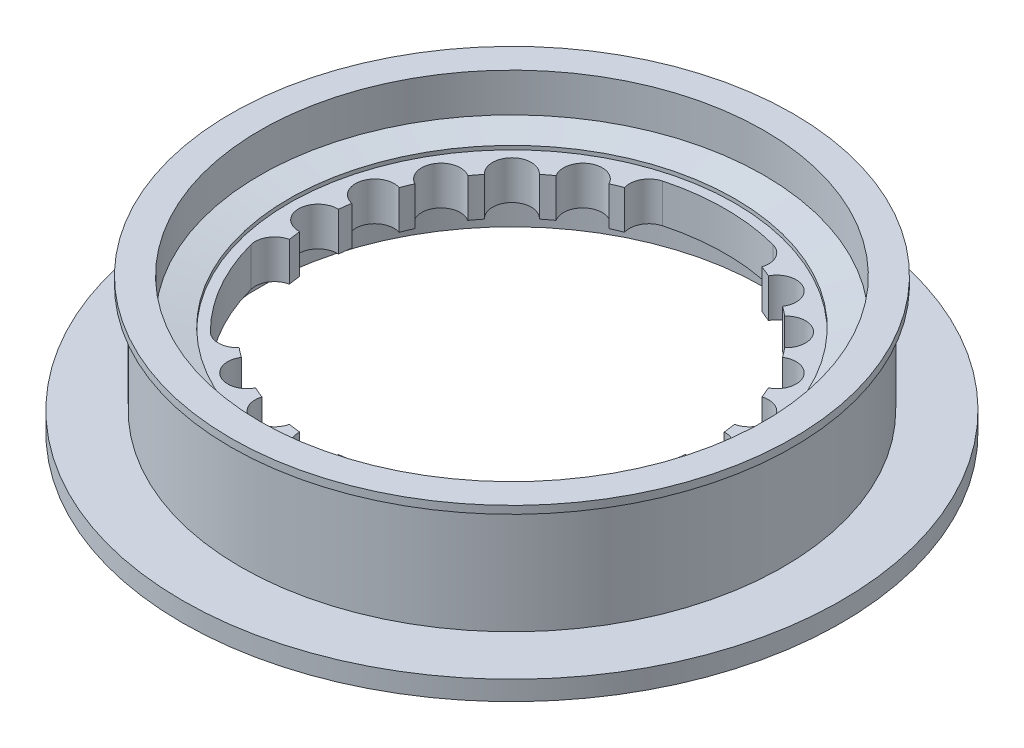
SolidWorks part; units mm, degrees
ref_plane "前视基准面" through (0, 0, 0) normal (0, 0, 1) x (1, 0, 0)
ref_plane "上视基准面" through (0, 0, 0) normal (0, 1, 0) x (1, 0, 0)
ref_plane "右视基准面" through (0, 0, 0) normal (1, 0, 0) x (0, 0, -1)
sketch "草图1" plane through (0, 0, 0) normal (0, 1, 0) x (1, 0, 0)
  circle A0 centre (0, 0) radius 17
  dimension "D1" = 34
extrude "凸台-拉伸1" add sketch "草图1" along normal blind 1
sketch "草图2" plane through (0, 1, 0) normal (0, 1, 0) x (1, 0, 0)
  circle A0 centre (0, 0) radius 14
  dimension "D1" = 28
extrude "凸台-拉伸2" add sketch "草图2" along normal blind 5.6
sketch "草图3" plane through (0, 6.6, 0) normal (0, 1, 0) x (1, 0, 0)
  circle A0 centre (0, 0) radius 14.5
  dimension "D1" = 29
extrude "凸台-拉伸3" add sketch "草图3" along normal blind 0.4
sketch "草图4" plane through (0, 0, 0) normal (1, 0, 0) x (0, 0, -1)
  line L0 (0, 0) -> (13, 0)
  line L1 (-17, 0) -> (17, 0) construction
  line L2 (13, 0) -> (13, 2)
  line L3 (13, 2) -> (11.5, 2.3)
  line L4 (11.5, 2.3) -> (11.5, 2.5)
  line L5 (11.5, 2.5) -> (0, 2.5)
  line L6 (0, 2.5) -> (0, 0)
  line L7 (0, 2.5) -> (0, 3.5) construction
  line L8 (0, 3.5) -> (5.9564, 3.5) construction
  line L9 (11.5, 4.7) -> (11.5, 4.5)
  line L10 (13, 5) -> (11.5, 4.7)
  line L11 (13, 7) -> (13, 5)
  line L12 (0, 7) -> (13, 7)
  line L13 (0, 4.5) -> (0, 7)
  line L14 (11.5, 4.5) -> (0, 4.5)
  dimension "D1" = 13
  dimension "D2" = 2
  dimension "D3" = 2.5
  dimension "D4" = 0.2
  dimension "D5" = 11.5
  dimension "D6" = 1
revolve "切除-旋转1" cut sketch "草图4" angle 360 about L13
sketch "草图5" plane through (0, 4.5, 0) normal (0, 1, 0) x (1, 0, 0)
  line L0 (0, 0) -> (0, 10) construction
  arc A0 (-3.54, 9.3525) -> (-4.1101, 9.1163) centre (0, 0) ccw
  arc A1 (-3.54, 9.3525) -> (-6.3295, 7.7419) centre (0, 0) ccw
  circle A2 centre (0, 10) radius 1 construction
  arc A3 (3.54, 9.3525) -> (2.847, 10.6252) centre (2.5882, 9.6593) ccw
  arc A4 (-9.1163, 4.1101) -> (-9.3525, 3.54) centre (0, 0) ccw
  arc A5 (5.8399, 8.1176) -> (4.1101, 9.1163) centre (5, 8.6603) ccw
  arc A6 (-9.95, -0.9987) -> (-9.8695, -1.6105) centre (0, 0) ccw
  arc A7 (7.7419, 6.3295) -> (6.3295, 7.7419) centre (7.0711, 7.0711) ccw
  arc A8 (-6.3295, -7.7419) -> (-5.8399, -8.1176) centre (0, 0) ccw
  arc A9 (9.1163, 4.1101) -> (8.1176, 5.8399) centre (8.6603, 5) ccw
  arc A10 (-1.6105, -9.8695) -> (-0.9987, -9.95) centre (0, 0) ccw
  arc A11 (9.8695, 1.6105) -> (9.3525, 3.54) centre (9.6593, 2.5882) ccw
  arc A12 (2.9237, -9.563) -> (4.1101, -9.1163) centre (0, 0) ccw
  arc A13 (9.95, -0.9987) -> (9.95, 0.9987) centre (10, 0) ccw
  arc A14 (9.95, 0.9987) -> (9.8695, 1.6105) centre (0, 0) ccw
  arc A15 (10.6252, -2.847) -> (9.8695, -1.6105) centre (9.6593, -2.5882) ccw
  arc A16 (7.7419, -6.3295) -> (8.1176, -5.8399) centre (0, 0) ccw
  arc A17 (9.8695, -1.6105) -> (9.95, -0.9987) centre (0, 0) ccw
  arc A18 (9.1163, -4.1101) -> (9.1163, 4.1101) centre (0, 0) ccw
  arc A19 (6.3295, -7.7419) -> (7.7782, -7.7782) centre (7.0711, -7.0711) ccw
  arc A20 (6.3295, 7.7419) -> (5.8399, 8.1176) centre (0, 0) ccw
  arc A21 (4.1101, -9.1163) -> (5.8399, -8.1176) centre (5, -8.6603) ccw
  arc A23 (1.6105, -9.8695) -> (3.54, -9.3525) centre (2.5882, -9.6593) ccw
  arc A25 (-0.9987, -9.95) -> (0.9987, -9.95) centre (0, -10) ccw
  circle A26 centre (0, 0) radius 10 construction
  arc A27 (-3.54, -9.3525) -> (-1.6105, -9.8695) centre (-2.5882, -9.6593) ccw
  circle A28 centre (0, 0) radius 10 construction
  arc A29 (-5.8399, -8.1176) -> (-4.1101, -9.1163) centre (-5, -8.6603) ccw
  circle A30 centre (0, 0) radius 10
  arc A31 (-7.7782, -7.7782) -> (-6.3295, -7.7419) centre (-7.0711, -7.0711) ccw
  circle A32 centre (0, 0) radius 10
  arc A33 (-4.1101, -9.1163) -> (-9.1163, -4.1101) centre (0, 0) ccw
  circle A34 centre (0, 0) radius 10
  arc A35 (-9.8695, -1.6105) -> (-10.6252, -2.847) centre (-9.6593, -2.5882) ccw
  circle A36 centre (0, 0) radius 10
  arc A37 (-9.95, 0.9987) -> (-9.95, -0.9987) centre (-10, 0) ccw
  circle A38 centre (0, 0) radius 10
  arc A39 (-9.3525, 3.54) -> (-9.8695, 1.6105) centre (-9.6593, 2.5882) ccw
  circle A40 centre (0, 0) radius 10
  arc A41 (-8.1176, 5.8399) -> (-9.1163, 4.1101) centre (-8.6603, 5) ccw
  circle A42 centre (0, 0) radius 10
  arc A43 (-6.3295, 7.7419) -> (-7.7419, 6.3295) centre (-7.0711, 7.0711) ccw
  circle A44 centre (0, 0) radius 10
  arc A45 (-4.1101, 9.1163) -> (-5.8399, 8.1176) centre (-5, 8.6603) ccw
  circle A46 centre (0, 0) radius 10
  arc A47 (-2.847, 10.6252) -> (-3.54, 9.3525) centre (-2.5882, 9.6593) ccw
  arc A48 (-10.6252, -2.847) -> (-7.7782, -7.7782) centre (0, 0) ccw
  arc A49 (0, 10) -> (-0.9987, 9.95) centre (0, 0) ccw
  arc A50 (-5.8399, 8.1176) -> (3.54, 9.3525) centre (0, 0) ccw
  arc A51 (-7.7419, 6.3295) -> (-0.9987, 9.95) centre (0, 0) ccw
  arc A52 (-9.8695, 1.6105) -> (-8.1176, 5.8399) centre (0, 0) ccw
  arc A53 (-9.1163, -4.1101) -> (-9.95, 0.9987) centre (0, 0) ccw
  arc A54 (-8.1176, -5.8399) -> (-9.1163, -4.1101) centre (-8.6603, -5) ccw [skipped]
  arc A55 (0.9987, -9.95) -> (-3.54, -9.3525) centre (0, 0) ccw
  arc A56 (5.8399, -8.1176) -> (1.6105, -9.8695) centre (0, 0) ccw
  arc A57 (9.1163, -4.1101) -> (6.3295, -7.7419) centre (0, 0) ccw
  arc A58 (9.5263, -5.5) -> (9.1163, -4.1101) centre (8.6603, -5) ccw [skipped]
  arc A59 (7.7419, -6.3295) -> (8.1176, -5.8399) centre (0, 0) ccw [skipped]
  arc A60 (9.3525, 3.54) -> (6.3295, -7.7419) centre (0, 0) ccw
  arc A61 (8.1176, 5.8399) -> (8.1176, -5.8399) centre (0, 0) ccw
  arc A62 (4.1101, 9.1163) -> (7.7419, 6.3295) centre (0, 0) ccw
  arc A63 (2.847, 10.6252) -> (-2.847, 10.6252) centre (0, 0) ccw
  arc A64 (7.7782, -7.7782) -> (10.6252, -2.847) centre (0, 0) ccw
  circle A65 centre (0, 0) radius 10 [skipped]
  circle A66 centre (0, 0) radius 10 [skipped]
  point P77 (0, 0)
  dimension "D1" = 2
  dimension "D3" = 24
extrude "切除-拉伸1" cut sketch "草图5" against normal up to next contours A40 A41 | A30 A39 | A36 A37 | A35 A48 A31 A32 A30 | A30 A43 | A1 A45 | A3 A63 A47 A30 A46 | A30 A5 | A30 A7 | A30 A9 | A18 A11 | A18 A13 | A19 A64 A15 A18 A30 A16 | A30 A21 | A30 A25 | A30 A27 | A30 A29 | A30 A23 A12 | A12 A30 A16 A18 A17 A14 A20 A46 A0 A1 A44 A42 A40 A4 A38 A36 A6 A32 A8 A10
